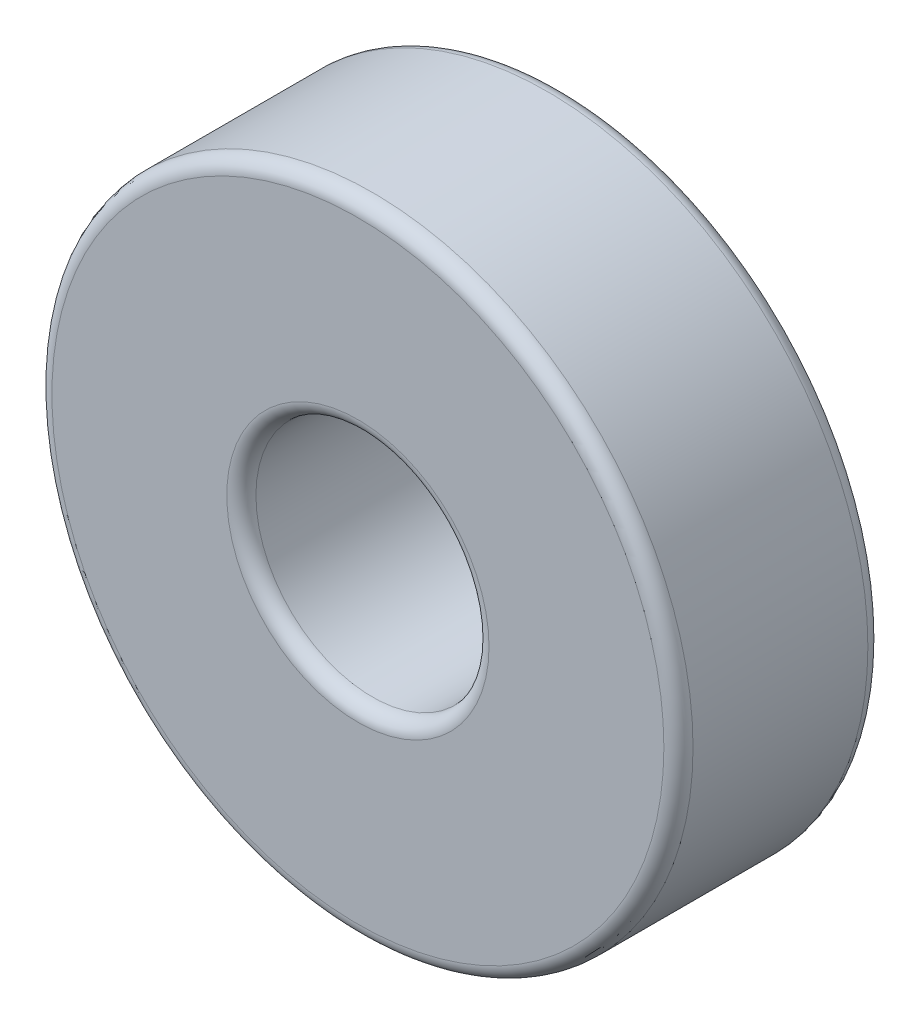
SolidWorks part; units mm, degrees
ref_plane "Front Plane" through (0, 0, 0) normal (0, 0, 1) x (1, 0, 0)
ref_plane "Top Plane" through (0, 0, 0) normal (0, 1, 0) x (1, 0, 0)
ref_plane "Right Plane" through (0, 0, 0) normal (1, 0, 0) x (0, 0, -1)
sketch "Sketch1" plane through (0, 0, 0) normal (0, 0, 1) x (1, 0, 0)
  circle A0 centre (0, 0) radius 4
  circle A1 centre (0, 0) radius 11
  dimension "D1" = 8
  dimension "D2" = 22
extrude "Boss-Extrude1" add sketch "Sketch1" along normal blind 7
fillet "Fillet1" radius 0.5 4 edges at (4, 0, 0) (4, 0, 7) (11, 0, 0) (11, 0, 7)
